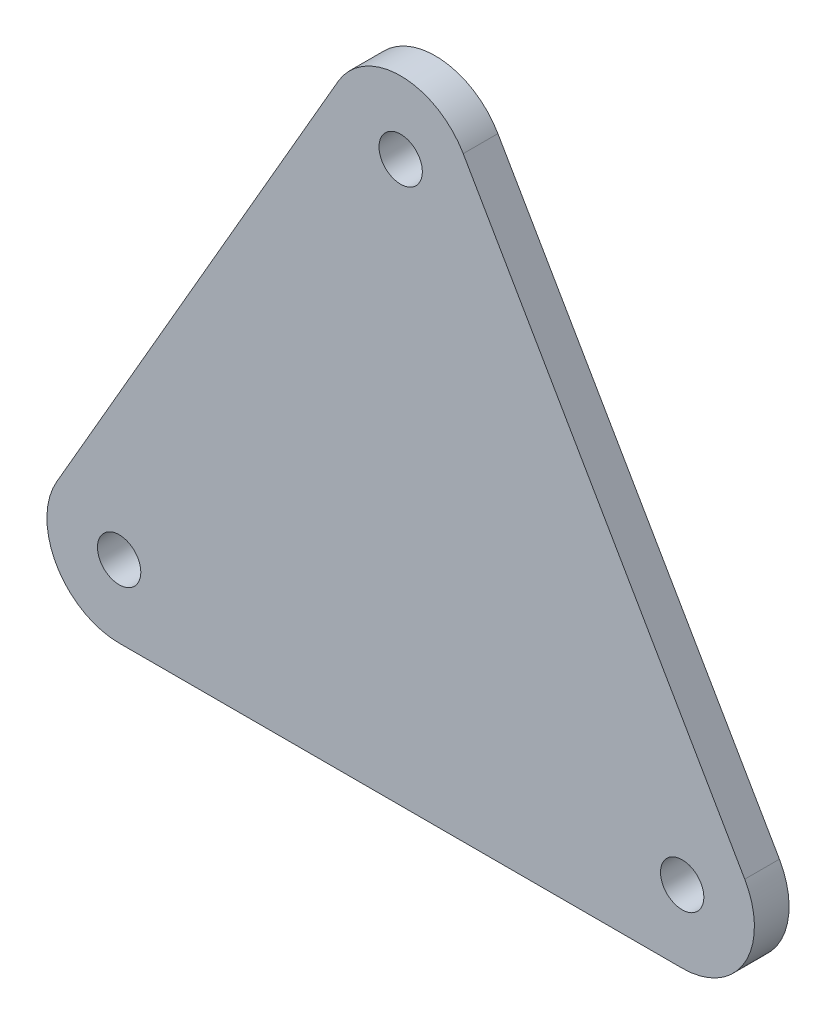
SolidWorks part; units mm, degrees
ref_plane "Front Plane" through (0, 0, 0) normal (0, 0, 1) x (1, 0, 0)
ref_plane "Top Plane" through (0, 0, 0) normal (0, 1, 0) x (1, 0, 0)
ref_plane "Right Plane" through (0, 0, 0) normal (1, 0, 0) x (0, 0, -1)
sketch "Sketch1" plane through (0, 0, 0) normal (0, 0, 1) x (1, 0, 0)
  line L0 (0, 0) -> (0, 22.5) construction
  line L7 (-23.8157, -8.75) -> (-4.3301, 25)
  line L8 (4.3301, 25) -> (23.8157, -8.75)
  line L9 (-19.4856, -16.25) -> (19.4856, -16.25)
  arc A8 (4.3301, 25) -> (-4.3301, 25) centre (0, 22.5) ccw
  circle A9 centre (0, 22.5) radius 1.5
  circle A10 centre (19.4856, -11.25) radius 1.5
  arc A11 (19.4856, -16.25) -> (23.8157, -8.75) centre (19.4856, -11.25) ccw
  circle A12 centre (-19.4856, -11.25) radius 1.5
  arc A13 (-23.8157, -8.75) -> (-19.4856, -16.25) centre (-19.4856, -11.25) ccw
  point P11 (0, 0)
  point P15 (0, 0)
  dimension "D2" = 3
  dimension "D1" = 22.5
extrude "Boss-Extrude1" add sketch "Sketch1" along normal blind 2.4
sketch "Sketch2" plane through (0, 0, 0) normal (0, 0, -1) x (-1, 0, 0)
  point P0 (0, 0)
sketch "Sketch3" plane through (0, 0, 0) normal (0, 0, -1) x (-1, 0, 0)
  circle A0 centre (0, 0) radius 3.4725 construction
  dimension "D1" = 6.945
